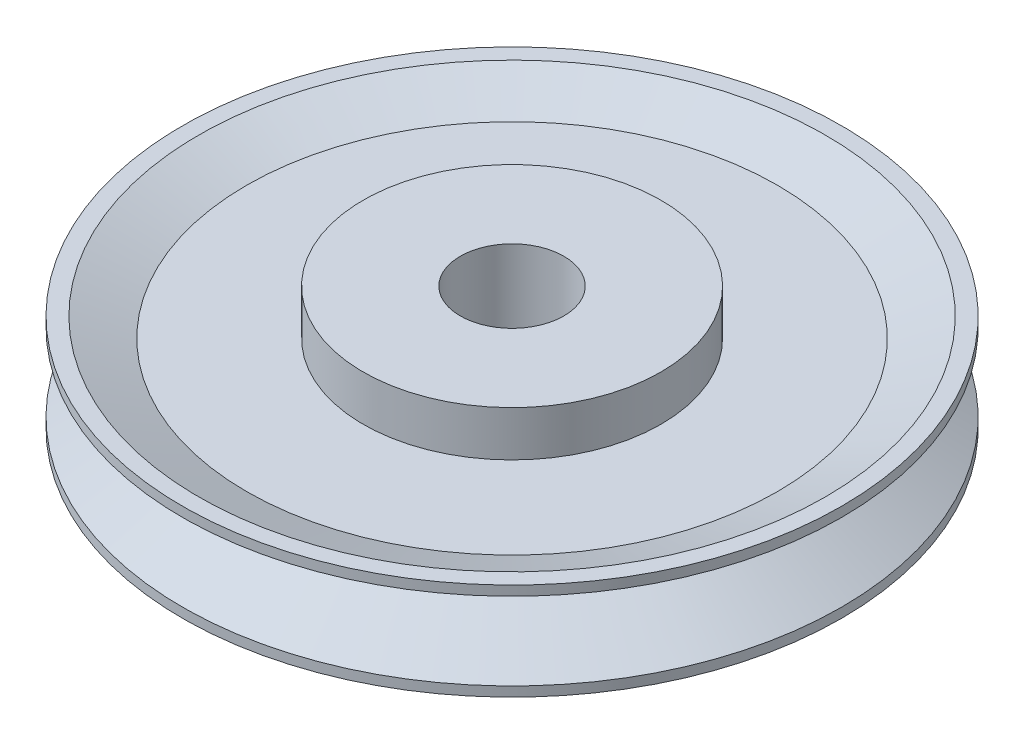
SolidWorks part; units mm, degrees
ref_plane "Front Plane" through (0, 0, 0) normal (0, 0, 1) x (1, 0, 0)
ref_plane "Top Plane" through (0, 0, 0) normal (0, 1, 0) x (1, 0, 0)
ref_plane "Right Plane" through (0, 0, 0) normal (1, 0, 0) x (0, 0, -1)
ref_plane "Plane1"
sketch "Sketch1" plane through (0, 0, 0) normal (0, 0, 1) x (1, 0, 0)
  line L0 (3.81, 2.2357) -> (0, 2.2357)
  line L1 (0, 2.2357) -> (0, -3.6063)
  line L2 (0, -3.6063) -> (3.81, -3.6063)
  line L3 (3.81, -3.6063) -> (3.81, -1.8283)
  line L4 (3.81, -1.8283) -> (3.81, 0.4577)
  line L5 (3.81, 0.4577) -> (3.81, 2.2357)
  line L6 (-2.032, -2.54) -> (-2.032, 2.54) construction
  line L7 (10.9007, -2.5903) -> (10.9007, -2.2093)
  line L8 (10.9007, -2.2093) -> (8.5205, -0.6853)
  line L9 (8.5205, -0.6853) -> (10.9007, 0.8387)
  line L10 (10.9007, 0.8387) -> (10.9007, 1.2197)
  line L11 (10.9007, 1.2197) -> (10.2657, 1.2197)
  line L12 (3.81, -1.8283) -> (8.382, -1.8283)
  line L13 (3.81, 0.4577) -> (3.81, -1.8283)
  line L14 (3.81, 0.4577) -> (8.382, 0.4577)
  line L15 (10.2657, -2.5903) -> (10.9007, -2.5903)
  line L16 (8.382, 0.4577) -> (10.2657, 1.2197)
  line L17 (8.382, -1.8283) -> (10.2657, -2.5903)
  dimension "D1" = 5.842
  dimension "D2" = 1.905
  dimension "D3" = 2.032
  dimension "D4" = 0.635
  dimension "D5" = 0.635
  dimension "D6" = 5.842
  dimension "D7" = 0.381
  dimension "D8" = 2.032
  dimension "D9" = 3.81
  dimension "D10" = 1.016
  dimension "D11" = 1.778
  dimension "D12" = 1.778
  dimension "D13" = 4.572
  dimension "D14" = 4.572
  dimension "D15" = 0.381
  dimension "D16" = 2.032
revolve "Revolution1" add sketch "Sketch1" angle 360 about L6
